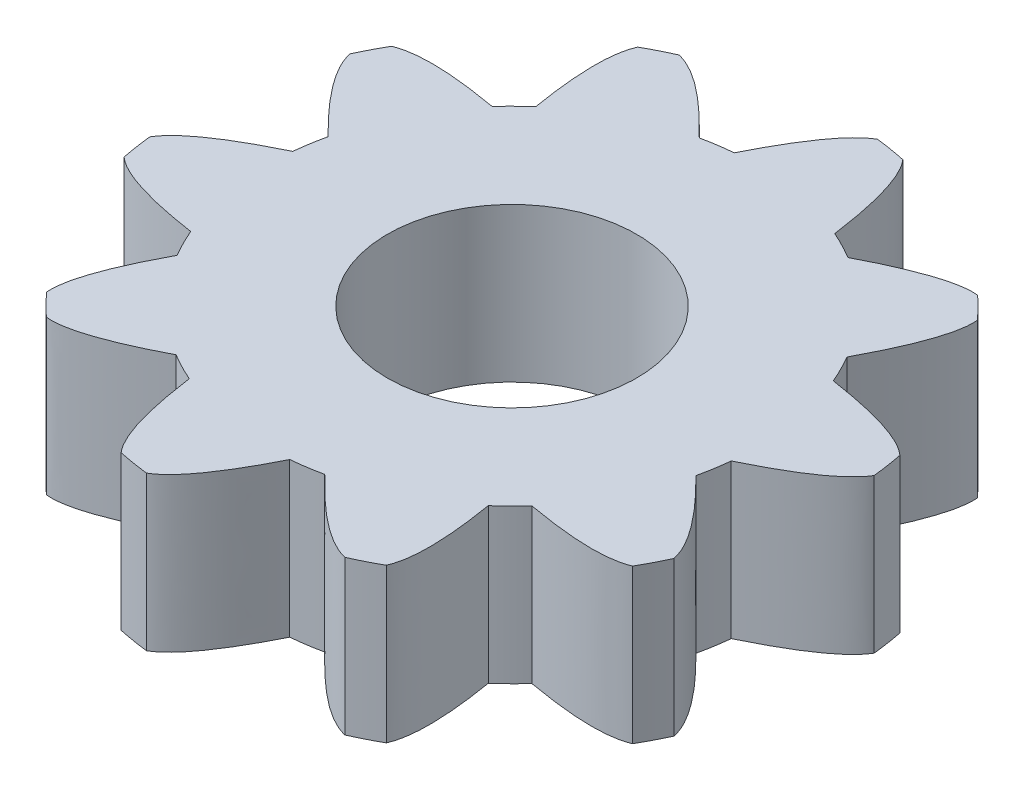
SolidWorks part; units mm, degrees
material "ABS"
ref_plane "Front Plane" through (0, 0, 0) normal (0, 0, 1) x (1, 0, 0)
ref_plane "Top Plane" through (0, 0, 0) normal (0, 1, 0) x (1, 0, 0)
ref_plane "Right Plane" through (0, 0, 0) normal (1, 0, 0) x (0, 0, -1)
sketch "Sketch1" plane through (0, 0, 0) normal (0, 1, 0) x (1, 0, 0)
  line L0 (4.0901, 6.8262) -> (6.8727, 4.0114) construction
  line L2 (5.4814, 5.4188) -> (7.6149, 7.5279) construction
  line L3 (7.6149, 7.5279) -> (7.7515, 7.6629)
  circle A0 centre (0, 0) radius 7.9577
  circle A1 centre (0, 0) radius 10.7077
  spline S0 degree 2 poles (6.8727, 4.0114) (10.0216, 9.9071) (4.0901, 6.8262) knots 0 0 0 1 1 1
  point P3 (4.0901, 6.8262)
  point P4 (6.8727, 4.0114)
  point P6 (7.2551, 7.8752)
  point P12 (3.2023, 7.285)
  point P14 (7.7515, 7.6629)
  point P15 (7.9581, 7.1641)
  point P16 (3.3638, 7.2119)
  dimension "D1" = 15.9155
  dimension "D4" = 3
  dimension "D5" = 1
  dimension "D2" = 4
  dimension "D3" = 1
extrude "Boss-Extrude4" add sketch "Sketch1" along normal blind 5 contours A0 | A0 S0 A1
pattern_circular "CirPattern6" count 10 every 36 of "Boss-Extrude4"
sketch "Sketch2" plane through (0, 5, 0) normal (0, 1, 0) x (1, 0, 0)
  circle A0 centre (0, 0) radius 4.05
  dimension "D1" = 8.1
extrude "Cut-Extrude1" cut sketch "Sketch2" against normal blind 10
sketch "Sketch3" plane through (0, 0, 0) normal (0, -1, 0) x (1, 0, 0)
equation "\"number-of-teeth\"= 10"
equation "\"gear-size\"= 4mm"
equation "\"circumference\"= \"number-of-teeth\" * ( ( 1 + \"space-between-teeth\" ) * \"gear-size\" )"
equation "\"space-between-teeth\"= .25"
equation "\"D1@Sketch1\" = \"circumference\" / pi"
equation "\"D2@Sketch1\"=\"gear-size\""
equation "\"gear-length\"= 3mm"
equation "\"D4@Sketch1\"=\"gear-length\""
equation "\"D5@Sketch1\"=\"gear-size\" * \"space-between-teeth\""
equation "\"D3@Sketch1\"=\"gear-size\" * \"space-between-teeth\""
equation "\"D1@CirPattern6\"=\"number-of-teeth\""
equation "\"D2@CirPattern6\"=360 / \"number-of-teeth\""
